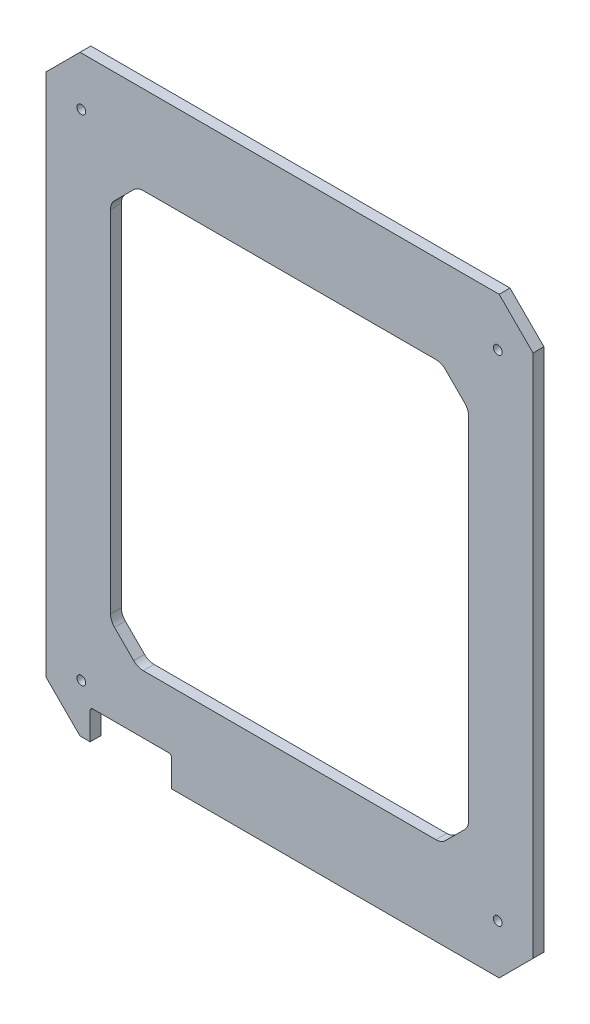
SolidWorks part; units mm, degrees
ref_plane "Front" through (0, 0, 0) normal (0, 0, 1) x (1, 0, 0)
ref_plane "Top" through (0, 0, 0) normal (0, 1, 0) x (1, 0, 0)
ref_plane "Right" through (0, 0, 0) normal (1, 0, 0) x (0, 0, -1)
ref_plane "Plane1" through (0, 0, 8) normal (0, 0, 1) x (1, 0, 0)
sketch "Sketch1" plane through (0, 0, 8) normal (0, 0, 1) x (1, 0, 0)
  line L0 (-154.5, -218.25) -> (154.5, -218.25)
  line L1 (154.5, -218.25) -> (179.5, -193.25)
  line L2 (179.5, -193.25) -> (179.5, 193.25)
  line L3 (179.5, 193.25) -> (154.5, 218.25)
  line L4 (154.5, 218.25) -> (-154.5, 218.25)
  line L5 (-154.5, 218.25) -> (-179.5, 193.25)
  line L6 (-179.5, 193.25) -> (-179.5, -193.25)
  line L7 (-179.5, -193.25) -> (-154.5, -218.25)
extrude "Boss-Extrude1" add sketch "Sketch1" against normal blind 8
sketch "Sketch2" plane through (0, 0, 0) normal (0, 0, -1) x (-1, 0, 0)
  line L0 (-107.8579, -153.25) -> (107.8579, -153.25)
  line L1 (114.9289, -150.3211) -> (129.0711, -136.1789)
  line L2 (132, -129.1079) -> (132, 129.1079)
  line L3 (129.0711, 136.1789) -> (114.9289, 150.3211)
  line L4 (107.8579, 153.25) -> (-107.8579, 153.25)
  line L5 (-114.9289, 150.3211) -> (-129.0711, 136.1789)
  line L6 (-132, 129.1079) -> (-132, -129.1079)
  line L7 (-129.0711, -136.1789) -> (-114.9289, -150.3211)
  arc A0 (107.8579, -153.25) -> (114.9289, -150.3211) centre (107.8579, -143.25) ccw
  arc A1 (129.0711, -136.1789) -> (132, -129.1079) centre (122, -129.1079) ccw
  arc A2 (132, 129.1079) -> (129.0711, 136.1789) centre (122, 129.1079) ccw
  arc A3 (114.9289, 150.3211) -> (107.8579, 153.25) centre (107.8579, 143.25) ccw
  arc A4 (-107.8579, 153.25) -> (-114.9289, 150.3211) centre (-107.8579, 143.25) ccw
  arc A5 (-129.0711, 136.1789) -> (-132, 129.1079) centre (-122, 129.1079) ccw
  arc A6 (-132, -129.1079) -> (-129.0711, -136.1789) centre (-122, -129.1079) ccw
  arc A7 (-114.9289, -150.3211) -> (-107.8579, -153.25) centre (-107.8579, -143.25) ccw
extrude "Cut-Extrude1" cut sketch "Sketch2" against normal through all
sketch "Sketch3" plane through (0, 0, 0) normal (0, 0, -1) x (-1, 0, 0)
  line L0 (134.25, -198.5) -> (124.25, -198.5)
  line L1 (122.25, -200.5) -> (122.25, -209.5)
  line L2 (124.25, -211.5) -> (134.25, -211.5)
  line L3 (136.25, -209.5) -> (136.25, -200.5)
  arc A0 (124.25, -198.5) -> (122.25, -200.5) centre (124.25, -200.5) ccw
  arc A1 (122.25, -209.5) -> (124.25, -211.5) centre (124.25, -209.5) ccw
  arc A2 (134.25, -211.5) -> (136.25, -209.5) centre (134.25, -209.5) ccw
  arc A3 (136.25, -200.5) -> (134.25, -198.5) centre (134.25, -200.5) ccw
extrude "Cut-Extrude2" cut sketch "Sketch3" against normal through all
hole_wizard "Ø6.5 (6.5) Diameter Hole2" positions "Sketch7" profile "Sketch6" hole size "Ø6.5" standard "ANSI Metric"
sketch "Sketch7" plane through (0, 0, 0) normal (0, 0, -1) x (-1, 0, 0)
  line L0 (0, 138.8018) -> (0, 0) construction
  line L1 (0, 0) -> (242.9826, 0) construction
  point P0 (-153.5, -182.25)
  point P1 (153.5, -182.25)
  point P2 (-153.5, 182.25)
  point P13 (153.5, 182.25)
  dimension "D1" = 182.25
  dimension "D2" = 307
sketch "Sketch6" plane through (153.5, -182.25, 0) normal (1, 0, 0) x (0, 1, 0)
  line L0 (0, 0) -> (0, 8)
  line L1 (0, 8) -> (3.25, 8)
  line L2 (3.25, 8) -> (3.25, 0)
  line L5 (3.25, 0) -> (0, 0)
  line L11 (0, -6.35) -> (0, 107.95) construction
  dimension "Thru Hole Dia." = 6.5
  dimension "Thru Hole Depth" = 8
sketch "Sketch8" plane through (0, 0, 8) normal (0, 0, 1) x (1, 0, 0)
  line L1 (-154.5, -218.25) -> (154.5, -218.25) construction
  line L2 (-179.5, 193.25) -> (-179.5, -193.25) construction
  line L3 (-117, -196.25) -> (-117, -227.87) construction
  line L9 (-89, -196.25) -> (-145, -196.25)
  line L10 (-87, -218.25) -> (-87, -198.25)
  line L11 (-147, -218.25) -> (-87, -218.25)
  line L12 (-147, -198.25) -> (-147, -218.25)
  arc A8 (-145, -196.25) -> (-147, -198.25) centre (-145, -198.25) ccw
  arc A9 (-87, -198.25) -> (-89, -196.25) centre (-89, -198.25) ccw
  dimension "D4" = 2
  dimension "D1" = 60
  dimension "D2" = 22
  dimension "D3" = 32.5
extrude "Cut-Extrude3" cut sketch "Sketch8" against normal up to next
